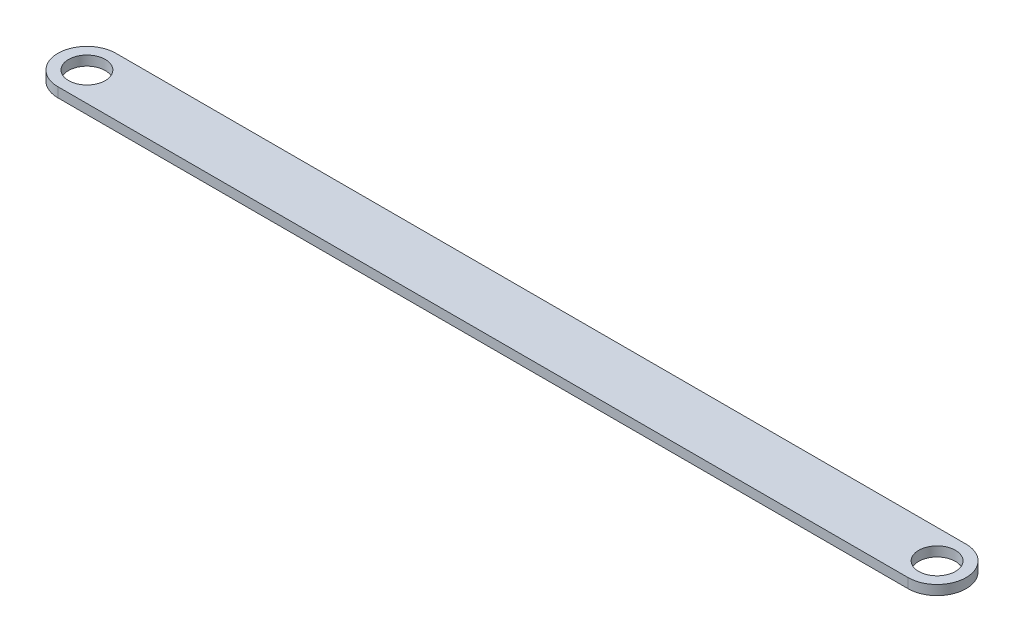
SolidWorks part; units mm, degrees
ref_plane "Alzado" through (0, 0, 0) normal (0, 0, 1) x (1, 0, 0)
ref_plane "Planta" through (0, 0, 0) normal (0, 1, 0) x (1, 0, 0)
ref_plane "Vista lateral" through (0, 0, 0) normal (1, 0, 0) x (0, 0, -1)
sketch "Croquis1" plane through (0, 0, 0) normal (0, 1, 0) x (1, 0, 0)
  line L0 (-110, 0) -> (110, 0) construction
  line L1 (-110, 7.5) -> (110, 7.5)
  line L2 (-110, -7.5) -> (110, -7.5)
  arc A0 (-110, 7.5) -> (-110, -7.5) centre (-110, 0) ccw
  arc A1 (110, -7.5) -> (110, 7.5) centre (110, 0) ccw
  point P2 (0, 0)
  dimension "D1" = 15
  dimension "D2" = 220
extrude "Saliente-Extruir1" add sketch "Croquis1" along normal blind 2.5
sketch "Croquis2" plane through (0, 2.5, 0) normal (0, 1, 0) x (1, 0, 0)
  line L0 (-117.5, 0) -> (117.5, 0) construction
  arc A0 (-110, 7.5) -> (-110, -7.5) centre (-110, 0) ccw construction
  arc A1 (110, -7.5) -> (110, 7.5) centre (110, 0) ccw construction
  circle A2 centre (-110, 0) radius 4.75
  circle A3 centre (110, 0) radius 4.75
  dimension "D1" = 9.5
extrude "Cortar-Extruir1" cut sketch "Croquis2" against normal through all
